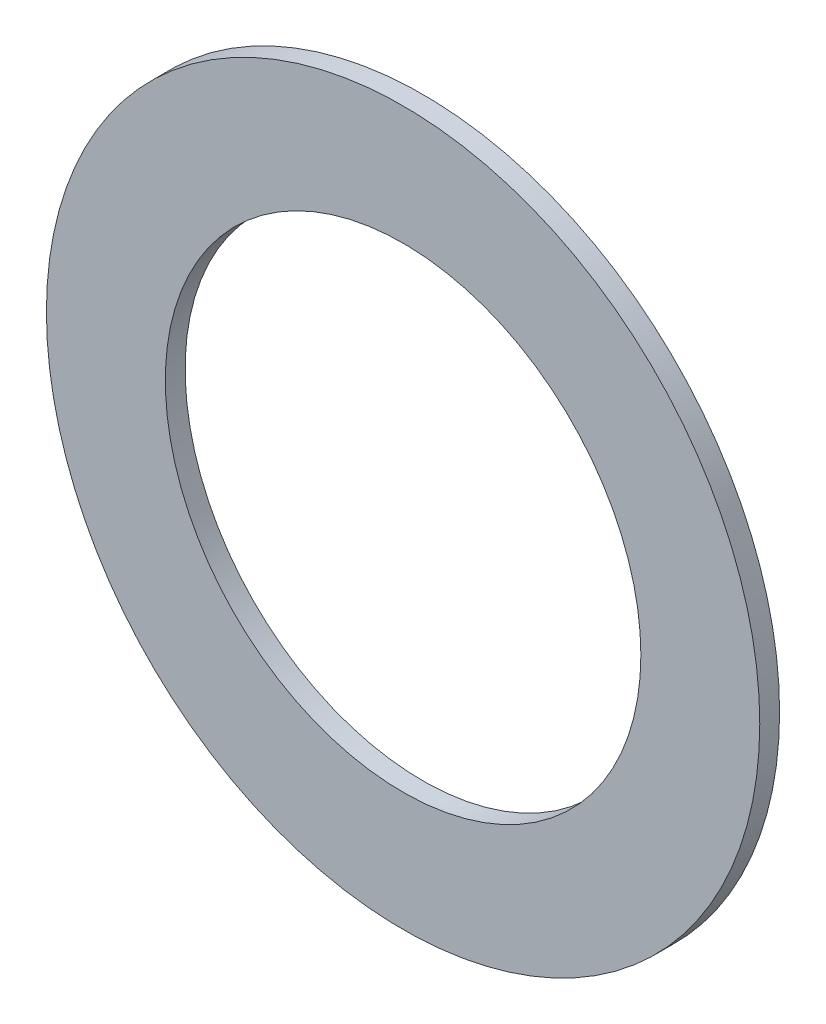
SolidWorks part; units mm, degrees
ref_plane "前视基准面" through (0, 0, 0) normal (0, 0, 1) x (1, 0, 0)
ref_plane "上视基准面" through (0, 0, 0) normal (0, 1, 0) x (1, 0, 0)
ref_plane "右视基准面" through (0, 0, 0) normal (1, 0, 0) x (0, 0, -1)
sketch "草图1" plane through (0, 0, 0) normal (0, 0, 1) x (1, 0, 0)
  circle A0 centre (0, 0) radius 6
  circle A1 centre (0, 0) radius 9
  dimension "D1" = 12
  dimension "D2" = 18
extrude "凸台-拉伸1" add sketch "草图1" along normal mid plane 0.5
